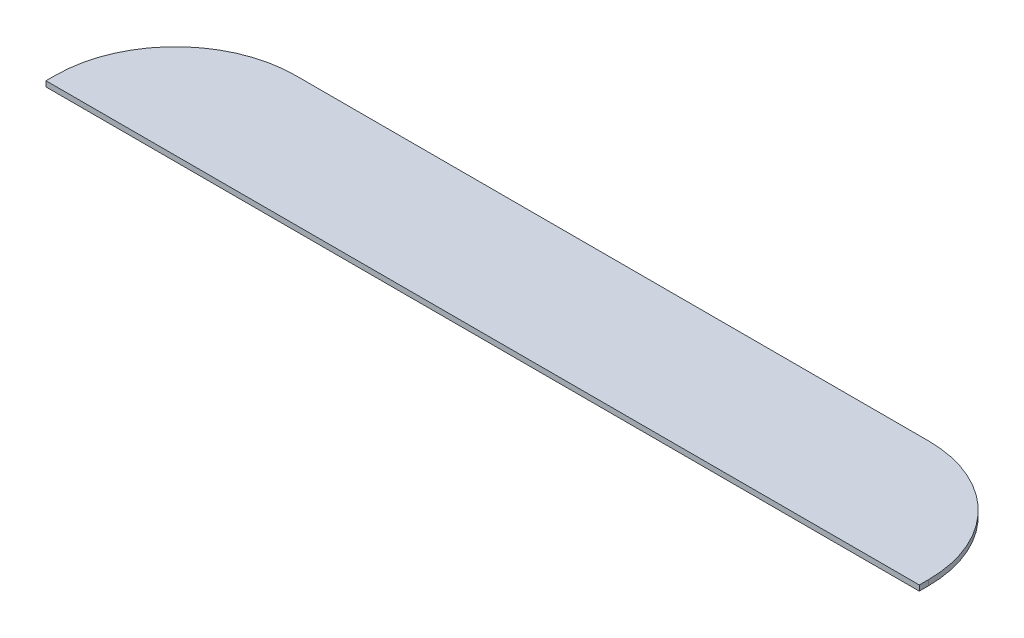
SolidWorks part; units mm, degrees
ref_plane "Front Plane" through (0, 0, 0) normal (0, 0, 1) x (1, 0, 0)
ref_plane "Top Plane" through (0, 0, 0) normal (0, 1, 0) x (1, 0, 0)
ref_plane "Right Plane" through (0, 0, 0) normal (1, 0, 0) x (0, 0, -1)
sketch "Sketch1" plane through (0, 0, 0) normal (0, 1, 0) x (1, 0, 0)
  line L0 (-257.175, 0) -> (257.175, 0)
  line L1 (-257.175, 0) -> (-257.175, 5.4)
  line L2 (-186.375, 76.2) -> (186.375, 76.2)
  line L3 (257.175, 5.4) -> (257.175, 0)
  arc A0 (186.375, 76.2) -> (257.175, 5.4) centre (186.375, 5.4) cw
  arc A1 (-257.175, 5.4) -> (-186.375, 76.2) centre (-186.375, 5.4) cw
  point P3 (0, 0)
  point P10 (-257.175, 76.2)
  dimension "D3" = 70.8
  dimension "D1" = 514.35
  dimension "D2" = 76.2
extrude "Boss-Extrude1" add sketch "Sketch1" along normal blind 3.175
